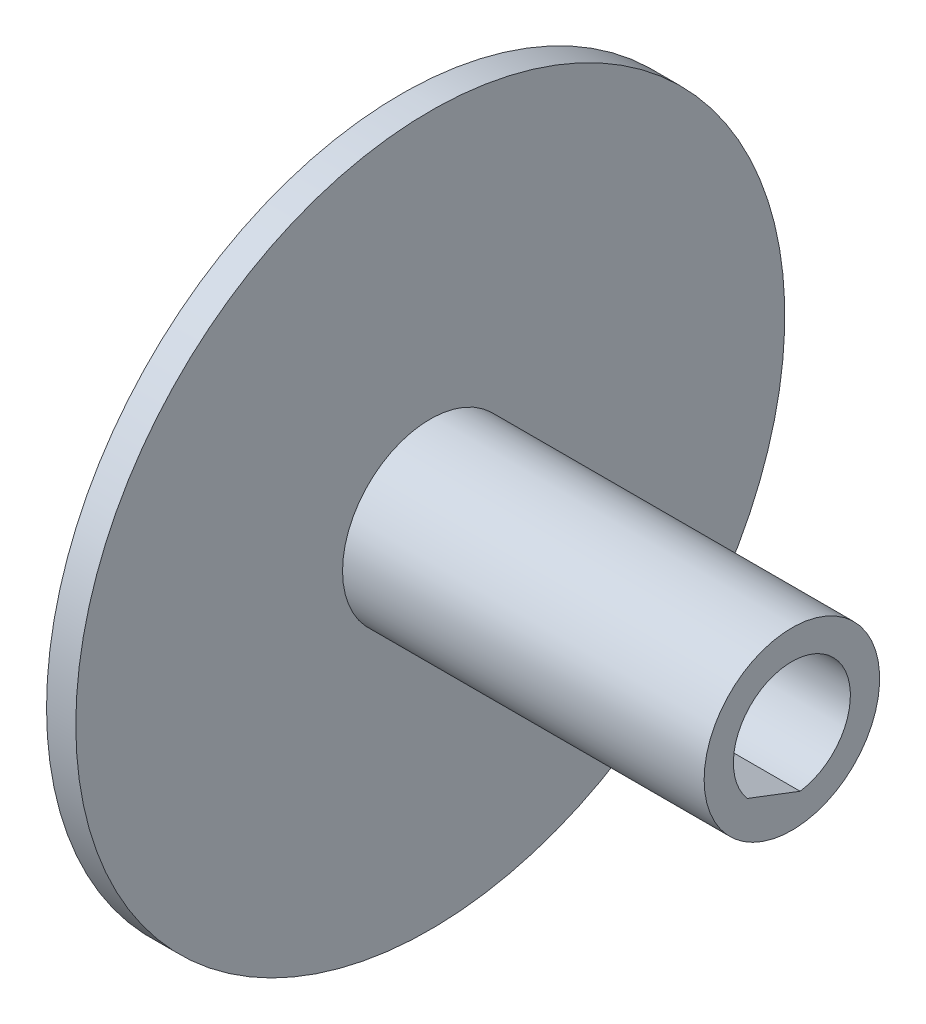
SolidWorks part; units mm, degrees
ref_plane "Front Plane" through (0, 0, 0) normal (0, 0, 1) x (1, 0, 0)
ref_plane "Top Plane" through (0, 0, 0) normal (0, 1, 0) x (1, 0, 0)
ref_plane "Right Plane" through (0, 0, 0) normal (1, 0, 0) x (0, 0, -1)
sketch "Sketch1" plane through (0, 0, 0) normal (0, 0, 1) x (1, 0, 0)
  line L0 (2, 5.0146) -> (2, 21.2538)
  line L1 (2, 5.0146) -> (2, 1.0146)
  line L2 (2, 1.0146) -> (7, 1.0146)
  line L3 (2, 21.2538) -> (4, 21.2538)
  line L4 (4, 21.2538) -> (4, 3.0146)
  line L5 (4, 3.0146) -> (7, 3.0146)
  line L6 (-0.1889, 4.5057) -> (4, 21.2538) construction
  line L7 (1.7514, 4.0205) -> (2, 5.0146) construction
  line L8 (7, 1.0146) -> (28.7228, 1.0146)
  line L9 (28.7228, 1.0146) -> (28.7228, 3.0146)
  line L10 (28.7228, 3.0146) -> (7, 3.0146)
  line L11 (2, -2.9854) -> (10.5552, -2.9854) construction
  dimension "D1" = 4
  dimension "D2" = 5
  dimension "D3" = 4
  dimension "D4" = 2
revolve "Revolve1" add sketch "Sketch1" angle 360 about L11
sketch "Sketch2" plane through (2, 0, 0) normal (-1, 0, 0) x (0, 0, 1)
  line L2 (-0.5617, -6.9458) -> (1.2476, -6.2555)
  line L3 (1.2476, -6.2555) -> (3.0569, -5.5652)
  arc A1 (-0.5617, -6.9458) -> (3.0569, -5.5652) centre (0, -2.9854) ccw
  dimension "D3" = 4
  dimension "D1" = 1.9365
  dimension "D2" = 1.9365
extrude "Boss-Extrude1" add sketch "Sketch2" against normal up to surface (26.7228 mm away) up to face at (28.7228, -2.9854, 6)
